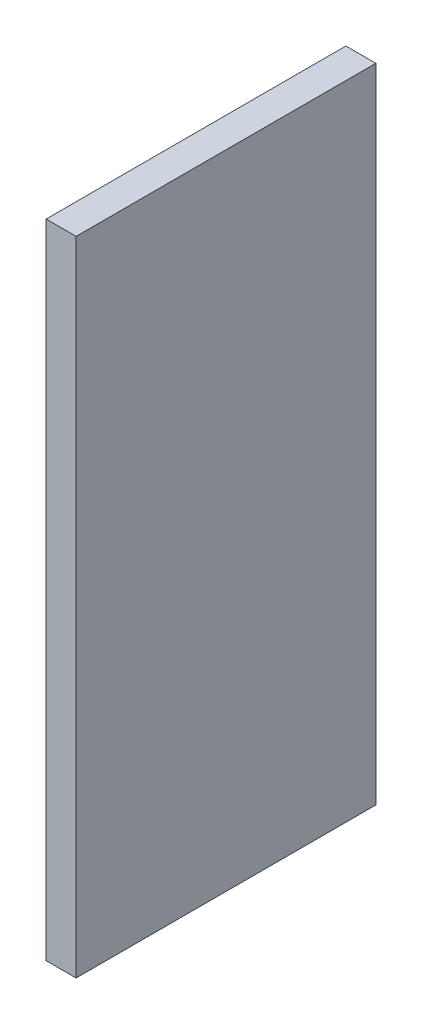
SolidWorks part; units mm, degrees
ref_plane "Front" through (0, 0, 0) normal (0, 0, 1) x (1, 0, 0)
ref_plane "Top" through (0, 0, 0) normal (0, 1, 0) x (1, 0, 0)
ref_plane "Right" through (0, 0, 0) normal (1, 0, 0) x (0, 0, -1)
sketch "Sketch1" plane through (0, 0, 0) normal (0, 0, 1) x (1, 0, 0)
  line L4 (0, 0) -> (7, 0)
  line L5 (7, 0) -> (7, 150)
  line L6 (7, 150) -> (0, 150)
  line L7 (0, 150) -> (0, 0)
  dimension "D1" = 150
  dimension "D2" = 7
extrude "Boss-Extrude1" add sketch "Sketch1" along normal blind 70
